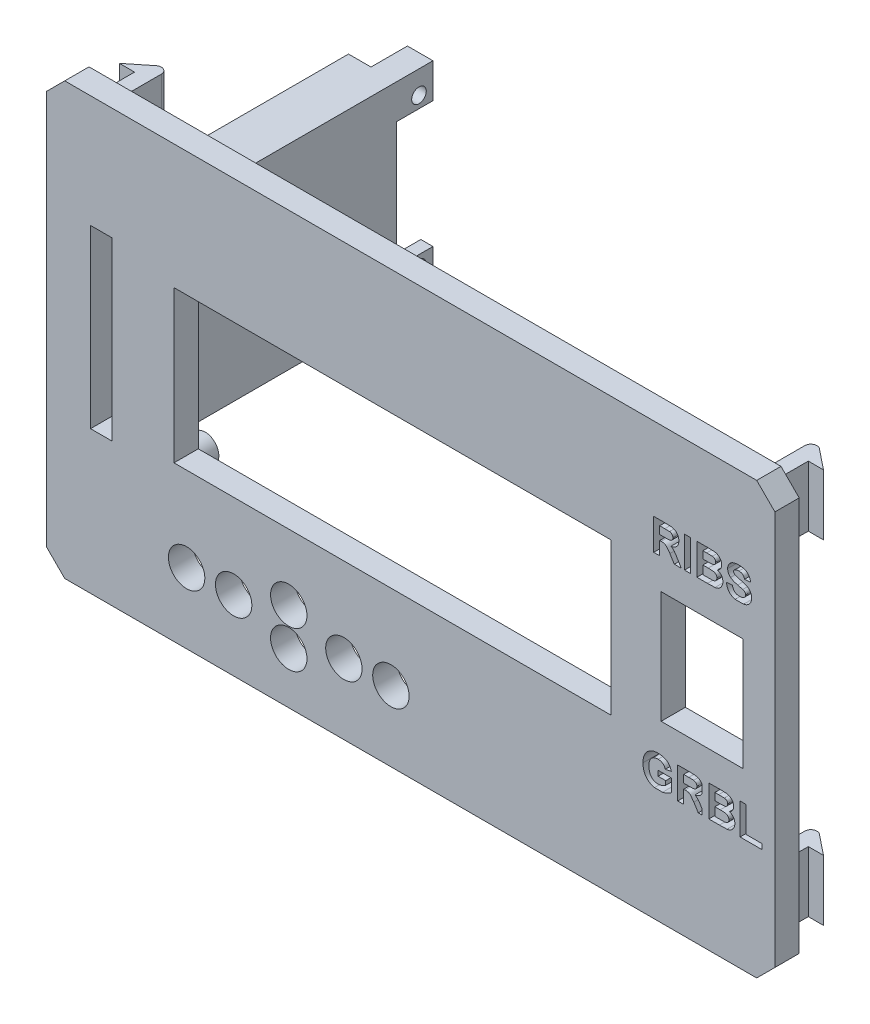
SolidWorks part; units mm, degrees
ref_plane "Спереди" through (0, 0, 0) normal (0, 0, 1) x (1, 0, 0)
ref_plane "Сверху" through (0, 0, 0) normal (0, 1, 0) x (1, 0, 0)
ref_plane "Справа" through (0, 0, 0) normal (1, 0, 0) x (0, 0, -1)
sketch "Эскиз1" plane through (0, 0, 0) normal (0, 0, 1) x (1, 0, 0)
  line L1 (-60, 30) -> (60, 30)
  line L2 (-60, 30) -> (-60, -30)
  line L3 (-60, -30) -> (60, -30)
  line L4 (60, 30) -> (60, -30)
  line L5 (-60, 30) -> (60, -30) construction
  line L6 (-60, -30) -> (60, 30) construction
  point P0 (0, 0)
  dimension "D1" = 120
  dimension "D2" = 60
extrude "Бобышка-Вытянуть1" add sketch "Эскиз1" along normal blind 4
sketch "Эскиз2" plane through (0, 0, 4) normal (0, 0, 1) x (1, 0, 0)
  line L0 (-60, 30) -> (-36, 30)
  line L1 (60, 30) -> (-60, 30) construction
  line L2 (-36, 30) -> (36, 30)
  line L3 (36, 30) -> (60, 30)
  line L4 (-36, 30) -> (-36, 12.5)
  line L5 (-36, 12.5) -> (-36, -12.5)
  line L6 (-36, -12.5) -> (-36, -30)
  line L7 (-60, -30) -> (60, -30) construction
  line L8 (-36, 12.5) -> (36, 12.5)
  line L9 (36, 12.5) -> (36, -12.5)
  line L10 (36, -12.5) -> (-36, -12.5)
  dimension "D1" = 72
  dimension "D2" = 25
extrude "Вырез-Вытянуть1" cut sketch "Эскиз2" against normal through all contours L10 L9 L8 L5
sketch "Эскиз3" plane through (0, 0, 4) normal (0, 0, 1) x (1, 0, 0)
  line L0 (51, 30) -> (51, -30)
  line L2 (51, 12.5) -> (51, 30)
  line L3 (60, 30) -> (-60, 30) construction
  line L4 (-60, -30) -> (60, -30) construction
  line L5 (51, 30) -> (60, 30)
  line L6 (44.25, 9.25) -> (57.75, 9.25)
  line L7 (44.25, 9.25) -> (44.25, -9.25)
  line L8 (44.25, -9.25) -> (57.75, -9.25)
  line L9 (57.75, 9.25) -> (57.75, -9.25)
  line L10 (44.25, 9.25) -> (57.75, -9.25) construction
  line L11 (44.25, -9.25) -> (57.75, 9.25) construction
  point P4 (51, 0)
  dimension "D1" = 13.5
  dimension "D2" = 18.5
  dimension "D3" = 9
extrude "Вырез-Вытянуть2" cut sketch "Эскиз3" against normal through all contours L9 L6 L0 L8 | L7 L8 L0 L6
sketch "Эскиз4" plane through (0, 0, 4) normal (0, 0, 1) x (1, 0, 0)
  line L0 (-60, 30) -> (-48, 30)
  line L1 (60, 30) -> (-60, 30) construction
  line L2 (-48, 30) -> (-48, -30)
  line L3 (-60, -30) -> (60, -30) construction
  line L5 (-49.75, 14.5) -> (-46.25, 14.5)
  line L6 (-49.75, 14.5) -> (-49.75, -14.5)
  line L7 (-49.75, -14.5) -> (-46.25, -14.5)
  line L8 (-46.25, 14.5) -> (-46.25, -14.5)
  line L9 (-49.75, 14.5) -> (-46.25, -14.5) construction
  line L10 (-49.75, -14.5) -> (-46.25, 14.5) construction
  point P8 (-48, 0)
  dimension "D1" = 12
  dimension "D2" = 3.5
  dimension "D3" = 29
extrude "Вырез-Вытянуть3" cut sketch "Эскиз4" against normal through all contours L8 L5 L2 L7 | L6 L7 L2 L5
sketch "Эскиз5" plane through (0, 30, 0) normal (0, 1, 0) x (1, 0, 0)
  line L1 (-60, 0) -> (60, 0)
  line L2 (-60, 0) -> (-60, -4)
  line L3 (-60, -4) -> (60, -4)
  line L4 (60, 0) -> (60, -4)
extrude "Бобышка-Вытянуть2" add sketch "Эскиз5" along normal blind 5
sketch "Эскиз6" plane through (0, -30, 0) normal (0, -1, 0) x (1, 0, 0)
  line L1 (-60, 0) -> (60, 0)
  line L2 (-60, 0) -> (-60, 4)
  line L3 (-60, 4) -> (60, 4)
  line L4 (60, 0) -> (60, 4)
extrude "Бобышка-Вытянуть3" add sketch "Эскиз6" along normal blind 10
sketch "Эскиз7" plane through (0, 0, 0) normal (0, 0, -1) x (-1, 0, 0)
  line L0 (60, -40) -> (33.92, -40)
  line L1 (60, -40) -> (-60, -40) construction
  line L2 (33.92, -40) -> (33.92, -26.42)
  circle A0 centre (33.92, -26.42) radius 2
  dimension "D3" = 4
  dimension "D1" = 26.08
  dimension "D2" = 13.58
extrude "Вырез-Вытянуть4" cut sketch "Эскиз7" against normal through all
sketch "Эскиз8" plane through (0, 0, 0) normal (0, 0, -1) x (-1, 0, 0)
  line L0 (33.92, -26.42) -> (26.173, -26.42)
  circle A0 centre (26.173, -26.42) radius 2
  dimension "D2" = 4
  dimension "D1" = 7.747
extrude "Вырез-Вытянуть5" cut sketch "Эскиз8" against normal through all
sketch "Эскиз10" plane through (0, 0, 0) normal (0, 0, -1) x (-1, 0, 0)
  line L0 (26.173, -26.42) -> (8.013, -26.42)
  line L1 (17.093, -26.42) -> (17.093, -29.4242)
  circle A0 centre (33.92, -26.42) radius 2
  circle A1 centre (26.173, -26.42) radius 2
  circle A2 centre (0.266, -26.42) radius 2
  circle A3 centre (8.013, -26.42) radius 2
  dimension "D1" = 18.16
extrude "Вырез-Вытянуть6" cut sketch "Эскиз10" against normal through all
sketch "Эскиз11" plane through (0, 0, 0) normal (0, 0, -1) x (-1, 0, 0)
  line L0 (26.173, -26.42) -> (8.013, -26.42)
  line L1 (17.093, -26.42) -> (17.093, -29.52)
  line L2 (17.093, -26.42) -> (17.093, -23.35)
  circle A0 centre (17.093, -29.52) radius 2
  circle A1 centre (17.093, -23.35) radius 2
  dimension "D3" = 4
  dimension "D4" = 4
  dimension "D1" = 3.07
  dimension "D2" = 3.1
extrude "Вырез-Вытянуть8" cut sketch "Эскиз11" against normal blind 10
sketch "Эскиз12" plane through (0, 0, 0) normal (0, 0, -1) x (-1, 0, 0)
  circle A0 centre (33.92, -26.42) radius 3
  circle A1 centre (26.173, -26.42) radius 3
  circle A2 centre (17.093, -29.52) radius 3
  circle A3 centre (17.093, -23.35) radius 3
  circle A4 centre (8.013, -26.42) radius 3
  circle A5 centre (0.266, -26.42) radius 3
  dimension "D1" = 6
extrude "Вырез-Вытянуть9" cut sketch "Эскиз12" against normal blind 10
sketch "Эскиз13" plane through (0, 0, 0) normal (0, 0, -1) x (-1, 0, 0)
  line L0 (46.25, -14.5) -> (37.86, -14.5)
  line L1 (37.86, -14.5) -> (37.86, -14.789)
  circle A0 centre (37.86, -14.789) radius 2.25
  circle A1 centre (-37.64, -14.789) radius 2.25
  circle A2 centre (-37.64, 16.711) radius 2.25
  circle A3 centre (37.86, 16.711) radius 2.25
  dimension "D2" = 4.5
  dimension "D1" = 8.39
  dimension "D3" = 2
  dimension "D4" = 2
extrude "Бобышка-Вытянуть4" add sketch "Эскиз13" along normal blind 3
sketch "Эскиз14" plane through (0, 0, 0) normal (0, 0, -1) x (-1, 0, 0)
  line L0 (37.86, 18.961) -> (-37.64, 18.961)
  line L1 (-37.64, 18.961) -> (-34.04, 18.961)
  line L2 (-34.04, 18.961) -> (-34.04, 15.961)
  line L3 (-34.04, 15.961) -> (34.26, 15.961)
  line L4 (34.26, 15.961) -> (34.26, 18.961)
  circle A0 centre (37.86, 16.711) radius 2.25 construction
  circle A1 centre (37.86, 16.711) radius 2.25 construction
  circle A2 centre (-37.64, 16.711) radius 2.25 construction
  circle A3 centre (-37.64, 16.711) radius 2.25 construction
  dimension "D1" = 3
  dimension "D2" = 3.6
  dimension "D3" = 3.6
extrude "Вырез-Вытянуть10" cut sketch "Эскиз14" against normal blind 2 contours L3 L4 L0 L2
sketch "Эскиз15" plane through (0, 0, -3) normal (0, 0, -1) x (-1, 0, 0)
  circle A0 centre (37.86, -14.789) radius 1.25
  circle A1 centre (37.86, 16.711) radius 1.25
  circle A2 centre (-37.64, 16.711) radius 1.25
  circle A3 centre (-37.64, -14.789) radius 1.25
  dimension "D1" = 2.5
extrude "Вырез-Вытянуть11" cut sketch "Эскиз15" against normal blind 6
sketch "Эскиз16" plane through (0, 0, 0) normal (0, 0, -1) x (-1, 0, 0)
  line L0 (49.75, -14.5) -> (49.75, 14.5)
  line L1 (51.25, 13.5693) -> (51.25, 16.2)
  line L2 (51.25, 13.5693) -> (51.25, -14.5)
  line L3 (49.75, 14.5) -> (45.3372, 14.5)
  line L4 (51.25, -14.5) -> (51.25, -16)
  line L5 (51.25, -16) -> (43.3372, -16)
  line L6 (43.3372, -16) -> (43.3372, 16.2)
  line L7 (51.25, 16.2) -> (43.3372, 16.2)
  line L8 (49.75, 14.5) -> (49.75, 14.7)
  line L9 (49.75, -14.5) -> (45.3372, -14.5)
  line L10 (45.3372, -14.5) -> (45.3372, 14.5)
  line L11 (49.75, 14.7) -> (45.3372, 14.7)
  line L12 (45.3372, 14.7) -> (45.3372, 14.5)
  line M40 (49.75, 14.5) -> (49.75, -14.5)
  line M41 (49.75, -14.5) -> (46.25, -14.5)
  dimension "D1" = 1.7
  dimension "D2" = 1.5
  dimension "D3" = 1.5
  dimension "D4" = 1.5
  dimension "D5" = 2
extrude "Бобышка-Вытянуть5" add sketch "Эскиз16" along normal blind 40 contours L1 L7 L6 L5 L4 L2 L12 L11 L8 L9 L10 M40 M41
sketch "Эскиз17" plane through (0, 0, -40) normal (0, 0, -1) x (-1, 0, 0)
  line L0 (47.5436, -14.5) -> (47.5436, -16)
  line L1 (49.75, -14.5) -> (45.3372, -14.5) construction
  line L2 (51.25, -16) -> (43.3372, -16) construction
  line L3 (47.5436, -16) -> (43.3372, -16)
  line L4 (43.3372, -16) -> (43.3372, -10.3)
  line L5 (43.3372, -16) -> (43.3372, 16.2) construction
  line L6 (43.3372, -10.3) -> (45.3372, -10.3)
  line L7 (45.3372, 14.7) -> (45.3372, -14.5) construction
  line L8 (45.3372, -10.3) -> (45.3372, -14.5)
  line L9 (45.3372, -14.5) -> (47.5436, -14.5)
  line L10 (45.3372, 0.1) -> (52.8332, 0.1)
  line L11 (45.3372, 14.7) -> (47.5436, 14.7)
  line L12 (45.3372, 10.5) -> (45.3372, 14.7)
  line L13 (43.3372, 10.5) -> (45.3372, 10.5)
  line L14 (43.3372, 16.2) -> (43.3372, 10.5)
  line L15 (47.5436, 16.2) -> (43.3372, 16.2)
  line L16 (47.5436, 14.7) -> (47.5436, 16.2)
  line M3 (45.3372, -14.5) -> (45.3372, 14.7)
  line M4 (45.3372, 14.7) -> (49.75, 14.7)
  line M6 (49.75, -14.5) -> (45.3372, -14.5)
  line M8 (51.25, 16.2) -> (43.3372, 16.2)
  line M9 (43.3372, 16.2) -> (43.3372, -16)
  line M10 (43.3372, -16) -> (51.25, -16)
  dimension "D1" = 5.7
extrude "Бобышка-Вытянуть6" add sketch "Эскиз17" along normal blind 6 contours L16 L13 M4 M8 M9 M3 | L6 L0 M9 M10 M6 M3
sketch "Эскиз18" plane through (-43.3372, 0, 0) normal (1, 0, 0) x (0, 0, -1)
  line L0 (46, -16) -> (43.7, -16)
  line L1 (46, -16) -> (0, -16) construction
  line L2 (43.7, -16) -> (43.7, 20.0976)
  line L3 (43.7, -16) -> (43.7, -12.216)
  line L4 (40, 0.1) -> (48.8407, 0.1)
  line L5 (40, -10.3) -> (40, 10.5) construction
  circle A0 centre (43.7, -12.216) radius 1.2
  circle A1 centre (43.7, 12.416) radius 1.2
  dimension "D3" = 2.4
  dimension "D1" = 2.3
  dimension "D2" = 3.784
extrude "Вырез-Вытянуть12" cut sketch "Эскиз18" against normal through all contours L2 A0 L3 | L3 A0 L2 | A1 L2 | A1 L2
sketch "Эскиз19" plane through (60, 0, 0) normal (1, 0, 0) x (0, 0, -1)
  line L1 (0, -40) -> (-4, -40)
  line L2 (0, -40) -> (0, 35)
  line L3 (0, 35) -> (-4, 35)
  line L4 (-4, -40) -> (-4, 35)
extrude "Бобышка-Вытянуть7" add sketch "Эскиз19" along normal blind 3
sketch "Эскиз20" plane through (-60, 0, 0) normal (-1, 0, 0) x (0, 0, 1)
  line L0 (0, 35) -> (4, 35) construction
  line L1 (4, -40) -> (0, -40)
  line L2 (4, -40) -> (4, 35)
  line L3 (4, 35) -> (0, 35)
  line L4 (0, -40) -> (0, 35)
extrude "Вырез-Вытянуть13" cut sketch "Эскиз20" against normal blind 3
sketch "Эскиз21" plane through (0, 0, 4) normal (0, 0, 1) x (1, 0, 0)
  line L0 (51, 9.25) -> (51, 14.25)
  line L1 (44.25, 9.25) -> (57.75, 9.25) construction
  line L2 (39.8485, 14.25) -> (62.1515, 14.25)
  line L3 (44.25, 0) -> (57.75, 0)
  line L4 (44.25, 9.25) -> (44.25, -9.25) construction
  line L5 (57.75, 9.25) -> (57.75, -9.25) construction
  line L6 (51, -9.25) -> (51, -19.25)
  line L7 (44.25, -9.25) -> (57.75, -9.25) construction
  line L8 (39.85, -19.25) -> (62.15, -19.25)
  line L9 (43.0316, 14.25) -> (43.0316, 19.3866)
  line L10 (43.0316, 19.3866) -> (45.1873, 19.3866)
  line L11 (46.953, 15.2666) -> (47.5756, 14.25)
  line L12 (47.5756, 14.25) -> (46.4211, 14.25)
  line L13 (46.4211, 14.25) -> (45.6905, 15.4158)
  line L14 (44.2407, 16.4232) -> (44.0194, 16.4232)
  line L15 (44.0194, 16.4232) -> (44.0194, 14.25)
  line L16 (44.0194, 14.25) -> (43.0316, 14.25)
  line L17 (44.0194, 17.2793) -> (44.8148, 17.2793)
  line L18 (44.8591, 18.5305) -> (44.0194, 18.5305)
  line L19 (44.0194, 18.5305) -> (44.0194, 17.2793)
  line L20 (48.1024, 14.25) -> (48.1024, 19.3866)
  line L21 (48.1024, 19.3866) -> (49.0902, 19.3866)
  line L22 (49.0902, 19.3866) -> (49.0902, 14.25)
  line L23 (49.0902, 14.25) -> (48.1024, 14.25)
  line L24 (50.1439, 19.3866) -> (52.2132, 19.3866)
  line L25 (51.8829, 14.25) -> (50.1439, 14.25)
  line L26 (50.1439, 14.25) -> (50.1439, 19.3866)
  line L27 (51.1317, 18.5305) -> (51.1317, 17.3452)
  line L28 (51.1317, 17.3452) -> (51.8468, 17.3452)
  line L29 (51.7584, 18.5305) -> (51.1317, 18.5305)
  line L30 (51.1317, 16.489) -> (51.1317, 15.1061)
  line L31 (51.1317, 15.1061) -> (52.1401, 15.1061)
  line L32 (52.0115, 16.489) -> (51.1317, 16.489)
  line L33 (55.0171, 15.9622) -> (56.0049, 16.0281)
  line L34 (58.9684, 17.9378) -> (57.9806, 17.872)
  line L35 (43.756, -17.3402) -> (43.756, -16.4841)
  line L36 (43.756, -16.4841) -> (45.9951, -16.4841)
  line L37 (45.9951, -16.4841) -> (45.9951, -18.5472)
  line L38 (45.9292, -15.5622) -> (44.9414, -15.7597)
  line L39 (45.0073, -18.0101) -> (45.0073, -17.3402)
  line L40 (45.0073, -17.3402) -> (43.756, -17.3402)
  line L41 (46.9829, -19.25) -> (46.9829, -14.1134)
  line L42 (46.9829, -14.1134) -> (49.1386, -14.1134)
  line L43 (50.9043, -18.2334) -> (51.5268, -19.25)
  line L44 (51.5268, -19.25) -> (50.3723, -19.25)
  line L45 (50.3723, -19.25) -> (49.6418, -18.0842)
  line L46 (48.1919, -17.0768) -> (47.9707, -17.0768)
  line L47 (47.9707, -17.0768) -> (47.9707, -19.25)
  line L48 (47.9707, -19.25) -> (46.9829, -19.25)
  line L49 (47.9707, -16.2207) -> (48.7661, -16.2207)
  line L50 (48.8103, -14.9695) -> (47.9707, -14.9695)
  line L51 (47.9707, -14.9695) -> (47.9707, -16.2207)
  line L52 (52.1195, -14.1134) -> (54.1888, -14.1134)
  line L53 (53.8585, -19.25) -> (52.1195, -19.25)
  line L54 (52.1195, -19.25) -> (52.1195, -14.1134)
  line L55 (53.1073, -14.9695) -> (53.1073, -16.1548)
  line L56 (53.1073, -16.1548) -> (53.8225, -16.1548)
  line L57 (53.734, -14.9695) -> (53.1073, -14.9695)
  line L58 (53.1073, -17.011) -> (53.1073, -18.3939)
  line L59 (53.1073, -18.3939) -> (54.1157, -18.3939)
  line L60 (53.9871, -17.011) -> (53.1073, -17.011)
  line L61 (57.2562, -19.25) -> (57.2562, -14.1134)
  line L62 (57.2562, -14.1134) -> (58.244, -14.1134)
  line L63 (58.244, -14.1134) -> (58.244, -18.3939)
  line L64 (58.244, -18.3939) -> (60.8781, -18.3939)
  line L65 (60.8781, -18.3939) -> (60.8781, -19.25)
  line L66 (60.8781, -19.25) -> (57.2562, -19.25)
  spline S0 degree 3 poles (45.1873, 19.3866) (45.3135, 19.386) (45.4963, 19.3844) (45.7301, 19.3679) (45.885, 19.3544) (46.0258, 19.3348) (46.1529, 19.3114) (46.2661, 19.2842) (46.3671, 19.2516) (46.4593, 19.2143) (46.5451, 19.17) (46.6255, 19.118) (46.7019, 19.0602) (46.7744, 18.9965) (46.8411, 18.9251) (46.9032, 18.8473) (46.9607, 18.7635) (47.0112, 18.6743) (47.0575, 18.5824) (47.0951, 18.4868) (47.1262, 18.3881) (47.151, 18.2864) (47.1744, 18.1449) (47.1809, 18.0365) (47.1804, 17.9636) knots 0 0 0 0 0.134568 0.194655 0.249727 0.300289 0.346032 0.387438 0.424316 0.459073 0.493245 0.527114 0.561039 0.595222 0.629875 0.664986 0.701286 0.737968 0.774262 0.810851 0.84727 0.884509 0.92231 1 1 1 1
  spline S1 degree 3 poles (47.1804, 17.9636) (47.1809, 17.8723) (47.1704, 17.7377) (47.1373, 17.5641) (47.1028, 17.4421) (47.0554, 17.3273) (47.0004, 17.2181) (46.9347, 17.1149) (46.8589, 17.0187) (46.773, 16.9294) (46.6766, 16.8489) (46.5705, 16.7768) (46.4539, 16.7136) (46.3278, 16.6596) (46.1414, 16.5973) (45.9938, 16.5667) (45.8922, 16.5508) knots 0 0 0 0 0.129362 0.190795 0.250525 0.308782 0.366645 0.423722 0.481911 0.540044 0.599083 0.659656 0.721689 0.786833 0.854049 1 1 1 1
  spline S2 degree 3 poles (45.8922, 16.5508) (45.9914, 16.4873) (46.1324, 16.3862) (46.2988, 16.2326) (46.3912, 16.1326) (46.4623, 16.0446) (46.5194, 15.9676) (46.5811, 15.879) (46.6467, 15.7788) (46.7181, 15.6678) (46.8218, 15.4963) (46.9001, 15.361) (46.953, 15.2666) knots 0 0 0 0 0.209649 0.307658 0.402219 0.451672 0.508779 0.572757 0.64366 0.721852 0.807549 1 1 1 1
  spline S3 degree 3 poles (45.6905, 15.4158) (45.6264, 15.505) (45.5349, 15.6323) (45.4158, 15.7911) (45.3413, 15.8916) (45.2732, 15.9769) (45.2135, 16.0487) (45.1634, 16.1083) (45.1067, 16.1674) (45.0408, 16.2281) (44.9592, 16.287) (44.8754, 16.334) (44.7856, 16.3698) (44.6818, 16.3948) (44.4991, 16.4182) (44.3489, 16.4245) (44.2407, 16.4232) knots 0 0 0 0 0.174865 0.249829 0.31616 0.3741 0.42377 0.464839 0.498075 0.554161 0.607388 0.658016 0.706819 0.760886 0.827647 1 1 1 1
  spline S4 degree 3 poles (44.8148, 17.2793) (44.9318, 17.2787) (45.0982, 17.282) (45.3081, 17.2864) (45.4381, 17.2941) (45.55, 17.3018) (45.6434, 17.3118) (45.7192, 17.3236) (45.7948, 17.3419) (45.8722, 17.3738) (45.9548, 17.4193) (46.0253, 17.4783) (46.0865, 17.5465) (46.1331, 17.6267) (46.1832, 17.7483) (46.1905, 17.8503) (46.1926, 17.9183) knots 0 0 0 0 0.20218 0.287584 0.36299 0.427194 0.481468 0.525327 0.559548 0.615694 0.669595 0.72182 0.77391 0.827085 0.881359 1 1 1 1
  spline S5 degree 3 poles (46.1926, 17.9183) (46.1917, 17.9941) (46.1784, 18.1071) (46.1144, 18.239) (46.0506, 18.3225) (45.9705, 18.3929) (45.8385, 18.4706) (45.7236, 18.5011) (45.6442, 18.5141) knots 0 0 0 0 0.256356 0.372788 0.488671 0.607002 0.72889 1 1 1 1
  spline S6 degree 3 poles (45.6442, 18.5141) (45.6118, 18.5183) (45.5544, 18.5209) (45.4672, 18.5249) (45.377, 18.5264) (45.2707, 18.5289) (45.0961, 18.5296) (44.9572, 18.5314) (44.8591, 18.5305) knots 0 0 0 0 0.124813 0.21921 0.333205 0.469464 0.625352 1 1 1 1
  spline S7 degree 3 poles (52.2132, 19.3866) (52.3092, 19.3858) (52.4485, 19.386) (52.6275, 19.3795) (52.747, 19.3755) (52.8563, 19.3661) (52.9562, 19.3587) (53.0465, 19.3486) (53.1529, 19.3321) (53.2766, 19.3066) (53.4163, 19.2593) (53.5487, 19.2003) (53.6719, 19.1252) (53.7862, 19.0374) (53.8925, 18.9375) (53.9859, 18.8216) (54.0701, 18.6951) (54.141, 18.5579) (54.2074, 18.3586) (54.227, 18.2007) (54.2269, 18.0942) knots 0 0 0 0 0.105884 0.153553 0.197457 0.237653 0.274456 0.307946 0.337788 0.393117 0.446926 0.500064 0.552657 0.605522 0.658748 0.713023 0.769236 0.826057 0.882736 1 1 1 1
  spline S8 degree 3 poles (54.2269, 18.0942) (54.2277, 17.9776) (54.2045, 17.8031) (54.1255, 17.5835) (54.043, 17.4299) (53.9417, 17.2889) (53.7817, 17.1228) (53.6357, 17.0282) (53.5313, 16.9799) knots 0 0 0 0 0.252157 0.376787 0.502926 0.628342 0.751132 1 1 1 1
  spline S9 degree 3 poles (53.5313, 16.9799) (53.6004, 16.9575) (53.7011, 16.9191) (53.8258, 16.8515) (53.9119, 16.7963) (53.9924, 16.7353) (54.0649, 16.6667) (54.1336, 16.5942) (54.194, 16.5142) (54.2486, 16.4306) (54.2949, 16.3421) (54.3351, 16.2507) (54.3686, 16.1556) (54.3925, 16.0562) (54.4185, 15.9178) (54.423, 15.8107) (54.4244, 15.7389) knots 0 0 0 0 0.132557 0.19578 0.258217 0.318868 0.379478 0.440087 0.500739 0.561785 0.621919 0.682673 0.743576 0.805446 0.868975 1 1 1 1
  spline S10 degree 3 poles (54.4244, 15.7389) (54.4237, 15.6231) (54.4048, 15.4477) (54.3353, 15.2222) (54.2649, 15.0565) (54.1773, 14.9002) (54.0744, 14.7576) (53.9543, 14.6334) (53.8213, 14.5241) (53.6714, 14.4336) (53.4431, 14.3379) (53.2567, 14.2984) (53.1279, 14.285) knots 0 0 0 0 0.162135 0.244884 0.329397 0.413636 0.495044 0.574817 0.654649 0.735398 0.818839 1 1 1 1
  spline S11 degree 3 poles (53.1279, 14.285) (53.0697, 14.2798) (52.971, 14.2728) (52.824, 14.2672) (52.68, 14.2617) (52.5129, 14.2578) (52.2447, 14.2539) (52.0321, 14.2505) (51.8829, 14.25) knots 0 0 0 0 0.140766 0.238316 0.354022 0.487867 0.640687 1 1 1 1
  spline S12 degree 3 poles (51.8468, 17.3452) (51.9429, 17.3444) (52.0794, 17.3459) (52.2516, 17.3469) (52.3583, 17.3488) (52.4498, 17.3521) (52.5415, 17.3558) (52.6026, 17.3585) (52.6381, 17.3626) knots 0 0 0 0 0.363929 0.517302 0.652498 0.76824 0.864499 1 1 1 1
  spline S13 degree 3 poles (52.6381, 17.3626) (52.7233, 17.3736) (52.8478, 17.3988) (52.9915, 17.4745) (53.0806, 17.5423) (53.1512, 17.6256) (53.2224, 17.7565) (53.2385, 17.8703) (53.239, 17.9461) knots 0 0 0 0 0.279181 0.403147 0.522445 0.638838 0.753413 1 1 1 1
  spline S14 degree 3 poles (53.239, 17.9461) (53.2409, 18.0195) (53.2235, 18.1269) (53.1644, 18.2553) (53.102, 18.3358) (53.0236, 18.4038) (52.8896, 18.4782) (52.7716, 18.5018) (52.6906, 18.513) knots 0 0 0 0 0.250586 0.366014 0.479792 0.596199 0.718553 1 1 1 1
  spline S15 degree 3 poles (52.6906, 18.513) (52.6509, 18.5173) (52.5819, 18.5199) (52.4773, 18.5236) (52.3703, 18.5269) (52.244, 18.5288) (52.0379, 18.5298) (51.8739, 18.5313) (51.7584, 18.5305) knots 0 0 0 0 0.12824 0.222081 0.336875 0.472602 0.628175 1 1 1 1
  spline S16 degree 3 poles (52.1401, 15.1061) (52.2293, 15.1044) (52.3565, 15.1079) (52.5171, 15.1094) (52.6176, 15.1142) (52.7044, 15.1179) (52.7935, 15.1235) (52.853, 15.1321) (52.8882, 15.138) knots 0 0 0 0 0.356994 0.509418 0.64271 0.759541 0.857263 1 1 1 1
  spline S17 degree 3 poles (52.8882, 15.138) (52.9649, 15.1503) (53.0748, 15.1871) (53.2039, 15.2669) (53.2863, 15.3419) (53.3539, 15.4318) (53.4216, 15.5767) (53.4371, 15.6999) (53.4366, 15.7832) knots 0 0 0 0 0.250408 0.369283 0.487615 0.607843 0.730168 1 1 1 1
  spline S18 degree 3 poles (53.4366, 15.7832) (53.437, 15.856) (53.4238, 15.9632) (53.3724, 16.0939) (53.3203, 16.1799) (53.2552, 16.2573) (53.1747, 16.3222) (53.0817, 16.3762) (52.9931, 16.4118) (52.9091, 16.4346) (52.8289, 16.4496) (52.7323, 16.4614) (52.6197, 16.4714) (52.4907, 16.4795) (52.2863, 16.4884) (52.1247, 16.4885) (52.0115, 16.489) knots 0 0 0 0 0.120696 0.176255 0.231267 0.286442 0.342925 0.401446 0.463858 0.500356 0.545451 0.598688 0.661396 0.732508 0.81263 1 1 1 1
  spline S19 degree 3 poles (56.0049, 16.0281) (56.018, 15.9473) (56.048, 15.8317) (56.0995, 15.6854) (56.1441, 15.5876) (56.193, 15.497) (56.2502, 15.4159) (56.3116, 15.342) (56.3803, 15.2778) (56.4552, 15.2216) (56.5366, 15.1736) (56.6236, 15.1321) (56.7165, 15.098) (56.8162, 15.0725) (56.9605, 15.0476) (57.0728, 15.0405) (57.1491, 15.0403) knots 0 0 0 0 0.146236 0.213456 0.277502 0.33853 0.397652 0.454745 0.510362 0.565639 0.622097 0.67924 0.738115 0.799044 0.863264 1 1 1 1
  spline S20 degree 3 poles (57.1491, 15.0403) (57.2293, 15.0395) (57.3457, 15.0464) (57.4951, 15.068) (57.5951, 15.0925) (57.6886, 15.12) (57.773, 15.1577) (57.8499, 15.2011) (57.919, 15.2503) (57.9793, 15.3049) (58.0321, 15.3619) (58.078, 15.4201) (58.1142, 15.482) (58.1434, 15.5452) (58.1695, 15.634) (58.1785, 15.7027) (58.1781, 15.7492) knots 0 0 0 0 0.172353 0.250759 0.324349 0.393928 0.460037 0.522848 0.58369 0.642236 0.697606 0.750761 0.801402 0.851621 0.900196 1 1 1 1
  spline S21 degree 3 poles (58.1781, 15.7492) (58.1795, 15.8066) (58.1655, 15.8908) (58.1208, 15.9937) (58.0716, 16.0625) (58.0054, 16.1253) (57.8845, 16.2096) (57.7744, 16.2534) (57.6966, 16.2822) knots 0 0 0 0 0.2213 0.325895 0.431605 0.54614 0.677623 1 1 1 1
  spline S22 degree 3 poles (57.6966, 16.2822) (57.657, 16.2962) (57.5891, 16.3154) (57.4892, 16.3444) (57.3923, 16.3715) (57.2803, 16.3992) (57.103, 16.4473) (56.9615, 16.4794) (56.8631, 16.5055) knots 0 0 0 0 0.145969 0.245215 0.361498 0.495676 0.646055 1 1 1 1
  spline S23 degree 3 poles (56.8631, 16.5055) (56.7325, 16.5358) (56.546, 16.5903) (56.3093, 16.67) (56.1547, 16.7322) (56.0148, 16.7952) (55.8571, 16.882) (55.7509, 16.9557) (55.689, 17.0097) knots 0 0 0 0 0.312041 0.452204 0.58122 0.699855 0.809224 1 1 1 1
  spline S24 degree 3 poles (55.689, 17.0097) (55.6139, 17.0774) (55.509, 17.1852) (55.3981, 17.3484) (55.3307, 17.4741) (55.2789, 17.6061) (55.2291, 17.7913) (55.2139, 17.9361) (55.2147, 18.0335) knots 0 0 0 0 0.260864 0.384835 0.506941 0.627504 0.749214 1 1 1 1
  spline S25 degree 3 poles (55.2147, 18.0335) (55.2135, 18.1606) (55.2423, 18.3513) (55.3337, 18.5915) (55.4124, 18.7345) (55.4883, 18.8427) (55.5512, 18.9204) (55.6204, 18.9931) (55.6967, 19.059) (55.7774, 19.1221) (55.8654, 19.178) (55.9585, 19.2308) (56.0931, 19.2933) (56.2759, 19.3584) (56.6045, 19.4346) (56.8659, 19.4517) (57.0452, 19.4525) knots 0 0 0 0 0.146314 0.219931 0.295355 0.333985 0.372228 0.410559 0.449522 0.48845 0.5285 0.569766 0.611707 0.699547 0.793005 1 1 1 1
  spline S26 degree 3 poles (57.0452, 19.4525) (57.1934, 19.453) (57.4091, 19.4414) (57.6851, 19.3982) (57.8709, 19.3535) (58.0419, 19.2943) (58.1987, 19.2239) (58.3413, 19.1402) (58.468, 19.0429) (58.5808, 18.9356) (58.6792, 18.8184) (58.7636, 18.6928) (58.8345, 18.5588) (58.8902, 18.4158) (58.9459, 18.2098) (58.9638, 18.0477) (58.9684, 17.9378) knots 0 0 0 0 0.161084 0.23435 0.303453 0.368554 0.430806 0.490159 0.547891 0.604075 0.659129 0.713948 0.768331 0.823595 0.880408 1 1 1 1
  spline S27 degree 3 poles (57.9806, 17.872) (57.9708, 17.9326) (57.9499, 18.02) (57.9124, 18.1298) (57.8805, 18.2032) (57.842, 18.2689) (57.8001, 18.3288) (57.7536, 18.3822) (57.7011, 18.4275) (57.6442, 18.4688) (57.5794, 18.5019) (57.5094, 18.5326) (57.4315, 18.5557) (57.3473, 18.574) (57.2222, 18.5927) (57.1245, 18.595) (57.0576, 18.5964) knots 0 0 0 0 0.140207 0.204905 0.264912 0.322857 0.378531 0.431843 0.484049 0.536898 0.59195 0.649895 0.711385 0.777189 0.846914 1 1 1 1
  spline S28 degree 3 poles (57.0576, 18.5964) (56.9875, 18.5956) (56.885, 18.592) (56.7535, 18.5718) (56.6635, 18.5528) (56.5796, 18.5268) (56.4775, 18.4855) (56.4072, 18.4446) (56.364, 18.4143) knots 0 0 0 0 0.288592 0.421401 0.547152 0.666859 0.782766 1 1 1 1
  spline S29 degree 3 poles (56.364, 18.4143) (56.3141, 18.3795) (56.2274, 18.2869) (56.2027, 18.1627) (56.2025, 18.1025) knots 0 0 0 0 0.502502 1 1 1 1
  spline S30 degree 3 poles (56.2025, 18.1025) (56.2012, 18.0451) (56.2297, 17.9273) (56.308, 17.8351) (56.3548, 17.7969) knots 0 0 0 0 0.485261 1 1 1 1
  spline S31 degree 3 poles (56.3548, 17.7969) (56.3949, 17.7639) (56.4697, 17.7222) (56.5825, 17.6702) (56.692, 17.6284) (56.8186, 17.5869) (56.9623, 17.5435) (57.1232, 17.4995) (57.2972, 17.4569) (57.4738, 17.415) (57.6424, 17.3692) (57.7992, 17.3245) (57.9433, 17.2778) (58.0757, 17.2322) (58.1957, 17.1854) (58.304, 17.1399) (58.4303, 17.0772) (58.5734, 16.9923) (58.7234, 16.869) (58.8561, 16.7303) (58.9486, 16.5996) (59.0121, 16.4871) (59.053, 16.3975) (59.0883, 16.303) (59.1171, 16.2036) (59.138, 16.0992) (59.1615, 15.9515) (59.1653, 15.8371) (59.1659, 15.7595) knots 0 0 0 0 0.040851 0.06742 0.098236 0.13339 0.172761 0.216898 0.265232 0.314356 0.360395 0.4033 0.443173 0.480216 0.513952 0.544926 0.573058 0.625371 0.67606 0.726118 0.776675 0.802168 0.82813 0.85447 0.881844 0.909815 0.938613 1 1 1 1
  spline S32 degree 3 poles (59.1659, 15.7595) (59.1657, 15.6872) (59.158, 15.5795) (59.1334, 15.4382) (59.1065, 15.3347) (59.0708, 15.2331) (59.0306, 15.132) (58.9803, 15.0336) (58.923, 14.9379) (58.8599, 14.8448) (58.7883, 14.759) (58.7125, 14.6775) (58.6277, 14.6049) (58.5391, 14.5354) (58.4426, 14.4738) (58.3405, 14.4181) (58.2322, 14.3687) (58.1172, 14.3256) (57.9957, 14.2872) (57.8667, 14.2558) (57.7311, 14.2289) (57.5886, 14.2085) (57.3852, 14.189) (57.2288, 14.1848) (57.1224, 14.1841) knots 0 0 0 0 0.074519 0.111158 0.147709 0.184737 0.222181 0.259833 0.298539 0.337199 0.375653 0.413687 0.45179 0.490635 0.529785 0.569677 0.610518 0.6525 0.696246 0.741804 0.789396 0.838723 0.890254 1 1 1 1
  spline S33 degree 3 poles (57.1224, 14.1841) (56.97, 14.1838) (56.7477, 14.1973) (56.4628, 14.2443) (56.2692, 14.2937) (56.0895, 14.3572) (55.9237, 14.4354) (55.7727, 14.5288) (55.6344, 14.6352) (55.5109, 14.7563) (55.3999, 14.8899) (55.3028, 15.037) (55.2196, 15.1974) (55.1485, 15.3702) (55.0681, 15.6234) (55.034, 15.8248) (55.0171, 15.9622) knots 0 0 0 0 0.148212 0.216241 0.280668 0.34231 0.401421 0.458656 0.514793 0.570722 0.626653 0.683482 0.741844 0.802144 0.865151 1 1 1 1
  spline S34 degree 3 poles (45.9951, -18.5472) (45.9382, -18.5999) (45.8468, -18.6764) (45.7118, -18.7675) (45.5992, -18.8352) (45.4783, -18.902) (45.3483, -18.9661) (45.2087, -19.0262) (45.0132, -19.1059) (44.7599, -19.1889) (44.3497, -19.2873) (44.0353, -19.3156) (43.827, -19.3159) knots 0 0 0 0 0.09909 0.152123 0.208003 0.267082 0.328665 0.393275 0.461354 0.598507 0.733703 1 1 1 1
  spline S35 degree 3 poles (43.827, -19.3159) (43.6986, -19.3155) (43.5081, -19.3069) (43.2604, -19.2708) (43.0837, -19.2331) (42.9127, -19.1877) (42.7483, -19.1298) (42.591, -19.0603) (42.4394, -18.9828) (42.2963, -18.8938) (42.1616, -18.7965) (42.0362, -18.6899) (41.9207, -18.574) (41.8134, -18.4494) (41.7155, -18.3156) (41.6278, -18.1725) (41.5491, -18.0217) (41.4791, -17.8647) (41.42, -17.7027) (41.3682, -17.5381) (41.3257, -17.3702) (41.2944, -17.1985) (41.2616, -16.9637) (41.255, -16.7843) (41.2536, -16.6642) knots 0 0 0 0 0.092398 0.13676 0.179854 0.222268 0.26384 0.30503 0.345839 0.386148 0.426054 0.465241 0.504301 0.543648 0.583355 0.623324 0.664248 0.705537 0.746812 0.788151 0.8296 0.871245 0.91355 1 1 1 1
  spline S36 degree 3 poles (41.2536, -16.6642) (41.2534, -16.535) (41.2635, -16.3434) (41.2974, -16.0931) (41.3352, -15.9136) (41.3812, -15.7393) (41.4374, -15.5701) (41.5062, -15.4074) (41.5828, -15.2498) (41.6699, -15.0995) (41.7684, -14.9583) (41.8753, -14.8249) (41.9927, -14.7014) (42.1202, -14.5878) (42.3034, -14.4465) (42.4521, -14.3542) (42.5573, -14.3017) knots 0 0 0 0 0.136153 0.201841 0.266068 0.329284 0.391808 0.453702 0.515293 0.576359 0.636621 0.696516 0.756344 0.81599 0.876288 1 1 1 1
  spline S37 degree 3 poles (42.5573, -14.3017) (42.6404, -14.2573) (42.7731, -14.2032) (42.9577, -14.1437) (43.1063, -14.1097) (43.2622, -14.0818) (43.4842, -14.0534) (43.6555, -14.0485) (43.7715, -14.0475) knots 0 0 0 0 0.225442 0.342643 0.464218 0.590259 0.721935 1 1 1 1
  spline S38 degree 3 poles (43.7715, -14.0475) (43.9202, -14.0479) (44.1381, -14.0574) (44.418, -14.1012) (44.6097, -14.145) (44.7885, -14.2014) (44.9541, -14.2707) (45.1075, -14.3515) (45.2465, -14.4471) (45.3739, -14.5526) (45.4894, -14.6679) (45.593, -14.7934) (45.6848, -14.9284) (45.764, -15.0734) (45.8565, -15.2815) (45.9043, -15.4482) (45.9292, -15.5622) knots 0 0 0 0 0.154508 0.225881 0.293868 0.358517 0.420293 0.480039 0.538219 0.595126 0.651534 0.707437 0.763839 0.820741 0.878777 1 1 1 1
  spline S39 degree 3 poles (44.9414, -15.7597) (44.9234, -15.6954) (44.8902, -15.6018) (44.8318, -15.4853) (44.783, -15.4038) (44.7278, -15.3278) (44.6651, -15.2579) (44.5986, -15.1911) (44.5242, -15.1319) (44.4449, -15.0786) (44.3616, -15.0305) (44.2724, -14.9915) (44.1785, -14.9601) (44.0805, -14.9335) (43.94, -14.911) (43.8318, -14.9021) (43.7581, -14.9036) knots 0 0 0 0 0.126732 0.187869 0.247151 0.306787 0.365822 0.425205 0.485392 0.545878 0.606517 0.667724 0.730306 0.794256 0.860288 1 1 1 1
  spline S40 degree 3 poles (43.7581, -14.9036) (43.6477, -14.905) (43.4849, -14.9147) (43.2773, -14.9616) (43.1338, -15.0088) (42.9987, -15.0694) (42.874, -15.1457) (42.7564, -15.2331) (42.6494, -15.3357) (42.5523, -15.4507) (42.4683, -15.5796) (42.3984, -15.7218) (42.3411, -15.8767) (42.2955, -16.0444) (42.2527, -16.2933) (42.2407, -16.4882) (42.2414, -16.622) knots 0 0 0 0 0.127318 0.186832 0.24467 0.301065 0.356888 0.412745 0.469466 0.527226 0.585734 0.646153 0.709402 0.775714 0.845921 1 1 1 1
  spline S41 degree 3 poles (42.2414, -16.622) (42.2412, -16.766) (42.2518, -16.9758) (42.2965, -17.2435) (42.343, -17.4235) (42.4014, -17.5896) (42.4717, -17.7424) (42.5584, -17.879) (42.6561, -18.0021) (42.7652, -18.1098) (42.8829, -18.2036) (43.0082, -18.2831) (43.1426, -18.3471) (43.2841, -18.398) (43.4881, -18.4467) (43.6478, -18.4598) (43.756, -18.4597) knots 0 0 0 0 0.160106 0.232808 0.301325 0.366436 0.428344 0.487788 0.545837 0.602718 0.657791 0.71279 0.767354 0.822823 0.879689 1 1 1 1
  spline S42 degree 3 poles (43.756, -18.4597) (43.8687, -18.4604) (44.0386, -18.4415) (44.2624, -18.3895) (44.4283, -18.3307) (44.5894, -18.2631) (44.7862, -18.1618) (44.9245, -18.0762) (45.0073, -18.0101) knots 0 0 0 0 0.249644 0.377965 0.509161 0.639801 0.765422 1 1 1 1
  spline S43 degree 3 poles (49.1386, -14.1134) (49.2648, -14.114) (49.4476, -14.1156) (49.6813, -14.1321) (49.8363, -14.1456) (49.977, -14.1652) (50.1041, -14.1886) (50.2174, -14.2158) (50.3184, -14.2484) (50.4105, -14.2857) (50.4963, -14.33) (50.5768, -14.382) (50.6531, -14.4398) (50.7256, -14.5035) (50.7924, -14.5749) (50.8545, -14.6527) (50.9119, -14.7365) (50.9625, -14.8257) (51.0087, -14.9176) (51.0464, -15.0132) (51.0774, -15.1119) (51.1022, -15.2136) (51.1256, -15.3551) (51.1322, -15.4635) (51.1317, -15.5364) knots 0 0 0 0 0.134568 0.194655 0.249727 0.300289 0.346032 0.387438 0.424316 0.459073 0.493245 0.527114 0.561039 0.595222 0.629875 0.664986 0.701286 0.737968 0.774262 0.810851 0.84727 0.884509 0.92231 1 1 1 1
  spline S44 degree 3 poles (51.1317, -15.5364) (51.1322, -15.6277) (51.1216, -15.7623) (51.0885, -15.9359) (51.0541, -16.0579) (51.0067, -16.1727) (50.9516, -16.2819) (50.886, -16.3851) (50.8102, -16.4813) (50.7243, -16.5706) (50.6279, -16.6511) (50.5218, -16.7232) (50.4052, -16.7864) (50.279, -16.8404) (50.0927, -16.9027) (49.9451, -16.9333) (49.8434, -16.9492) knots 0 0 0 0 0.129362 0.190795 0.250525 0.308782 0.366645 0.423722 0.481911 0.540044 0.599083 0.659656 0.721689 0.786833 0.854049 1 1 1 1
  spline S45 degree 3 poles (49.8434, -16.9492) (49.9426, -17.0127) (50.0837, -17.1138) (50.25, -17.2674) (50.3425, -17.3674) (50.4135, -17.4554) (50.4707, -17.5324) (50.5324, -17.621) (50.598, -17.7212) (50.6694, -17.8322) (50.773, -18.0037) (50.8513, -18.139) (50.9043, -18.2334) knots 0 0 0 0 0.209649 0.307658 0.402219 0.451672 0.508779 0.572757 0.64366 0.721852 0.807549 1 1 1 1
  spline S46 degree 3 poles (49.6418, -18.0842) (49.5777, -17.995) (49.4862, -17.8677) (49.3671, -17.7089) (49.2926, -17.6084) (49.2245, -17.5231) (49.1647, -17.4513) (49.1147, -17.3917) (49.058, -17.3326) (48.9921, -17.2719) (48.9105, -17.213) (48.8267, -17.166) (48.7369, -17.1302) (48.6331, -17.1052) (48.4503, -17.0818) (48.3002, -17.0755) (48.1919, -17.0768) knots 0 0 0 0 0.174865 0.249829 0.31616 0.3741 0.42377 0.464839 0.498075 0.554161 0.607388 0.658016 0.706819 0.760886 0.827647 1 1 1 1
  spline S47 degree 3 poles (48.7661, -16.2207) (48.8831, -16.2213) (49.0494, -16.218) (49.2594, -16.2136) (49.3894, -16.2059) (49.5013, -16.1982) (49.5947, -16.1882) (49.6704, -16.1764) (49.746, -16.1581) (49.8235, -16.1262) (49.906, -16.0807) (49.9766, -16.0217) (50.0377, -15.9535) (50.0843, -15.8733) (50.1345, -15.7517) (50.1418, -15.6497) (50.1439, -15.5817) knots 0 0 0 0 0.20218 0.287584 0.36299 0.427194 0.481468 0.525327 0.559548 0.615694 0.669595 0.72182 0.77391 0.827085 0.881359 1 1 1 1
  spline S48 degree 3 poles (50.1439, -15.5817) (50.1429, -15.5059) (50.1297, -15.3929) (50.0656, -15.261) (50.0019, -15.1775) (49.9217, -15.1071) (49.7897, -15.0294) (49.6749, -14.9989) (49.5955, -14.9859) knots 0 0 0 0 0.256356 0.372788 0.488671 0.607002 0.72889 1 1 1 1
  spline S49 degree 3 poles (49.5955, -14.9859) (49.563, -14.9817) (49.5056, -14.9791) (49.4185, -14.9751) (49.3283, -14.9736) (49.2219, -14.9711) (49.0473, -14.9704) (48.9084, -14.9686) (48.8103, -14.9695) knots 0 0 0 0 0.124813 0.21921 0.333205 0.469464 0.625352 1 1 1 1
  spline S50 degree 3 poles (54.1888, -14.1134) (54.2848, -14.1142) (54.4241, -14.114) (54.6031, -14.1205) (54.7226, -14.1245) (54.8319, -14.1339) (54.9319, -14.1413) (55.0221, -14.1514) (55.1285, -14.1679) (55.2522, -14.1934) (55.3919, -14.2407) (55.5243, -14.2997) (55.6475, -14.3748) (55.7618, -14.4626) (55.8681, -14.5625) (55.9615, -14.6784) (56.0457, -14.8049) (56.1166, -14.9421) (56.183, -15.1414) (56.2026, -15.2993) (56.2025, -15.4058) knots 0 0 0 0 0.105884 0.153553 0.197457 0.237653 0.274456 0.307946 0.337788 0.393117 0.446926 0.500064 0.552657 0.605522 0.658748 0.713023 0.769236 0.826057 0.882736 1 1 1 1
  spline S51 degree 3 poles (56.2025, -15.4058) (56.2033, -15.5224) (56.1802, -15.6969) (56.1012, -15.9165) (56.0186, -16.0701) (55.9173, -16.2111) (55.7573, -16.3772) (55.6113, -16.4718) (55.5069, -16.5201) knots 0 0 0 0 0.252157 0.376787 0.502926 0.628342 0.751132 1 1 1 1
  spline S52 degree 3 poles (55.5069, -16.5201) (55.576, -16.5425) (55.6768, -16.5809) (55.8015, -16.6485) (55.8876, -16.7037) (55.968, -16.7647) (56.0405, -16.8333) (56.1093, -16.9058) (56.1696, -16.9858) (56.2242, -17.0694) (56.2705, -17.1579) (56.3107, -17.2493) (56.3443, -17.3444) (56.3682, -17.4438) (56.3941, -17.5822) (56.3986, -17.6893) (56.4001, -17.7611) knots 0 0 0 0 0.132557 0.19578 0.258217 0.318868 0.379478 0.440087 0.500739 0.561785 0.621919 0.682673 0.743576 0.805446 0.868975 1 1 1 1
  spline S53 degree 3 poles (56.4001, -17.7611) (56.3994, -17.8769) (56.3804, -18.0523) (56.3109, -18.2778) (56.2405, -18.4435) (56.1529, -18.5998) (56.05, -18.7424) (55.9299, -18.8666) (55.7969, -18.9759) (55.6471, -19.0664) (55.4188, -19.1621) (55.2323, -19.2016) (55.1035, -19.215) knots 0 0 0 0 0.162135 0.244884 0.329397 0.413636 0.495044 0.574817 0.654649 0.735398 0.818839 1 1 1 1
  spline S54 degree 3 poles (55.1035, -19.215) (55.0453, -19.2202) (54.9466, -19.2272) (54.7997, -19.2328) (54.6556, -19.2383) (54.4886, -19.2422) (54.2204, -19.2461) (54.0077, -19.2495) (53.8585, -19.25) knots 0 0 0 0 0.140766 0.238316 0.354022 0.487867 0.640687 1 1 1 1
  spline S55 degree 3 poles (53.8225, -16.1548) (53.9185, -16.1556) (54.055, -16.1541) (54.2272, -16.1531) (54.3339, -16.1512) (54.4255, -16.1479) (54.5171, -16.1442) (54.5782, -16.1415) (54.6138, -16.1374) knots 0 0 0 0 0.363929 0.517302 0.652498 0.76824 0.864499 1 1 1 1
  spline S56 degree 3 poles (54.6138, -16.1374) (54.699, -16.1264) (54.8234, -16.1012) (54.9671, -16.0255) (55.0562, -15.9577) (55.1268, -15.8744) (55.198, -15.7435) (55.2141, -15.6297) (55.2147, -15.5539) knots 0 0 0 0 0.279181 0.403147 0.522445 0.638838 0.753413 1 1 1 1
  spline S57 degree 3 poles (55.2147, -15.5539) (55.2165, -15.4805) (55.1991, -15.3731) (55.14, -15.2447) (55.0776, -15.1642) (54.9993, -15.0962) (54.8652, -15.0218) (54.7472, -14.9982) (54.6662, -14.987) knots 0 0 0 0 0.250586 0.366014 0.479792 0.596199 0.718553 1 1 1 1
  spline S58 degree 3 poles (54.6662, -14.987) (54.6266, -14.9827) (54.5576, -14.9801) (54.4529, -14.9764) (54.3459, -14.9731) (54.2197, -14.9712) (54.0135, -14.9702) (53.8496, -14.9687) (53.734, -14.9695) knots 0 0 0 0 0.12824 0.222081 0.336875 0.472602 0.628175 1 1 1 1
  spline S59 degree 3 poles (54.1157, -18.3939) (54.2049, -18.3956) (54.3322, -18.3921) (54.4927, -18.3906) (54.5932, -18.3858) (54.68, -18.3821) (54.7691, -18.3765) (54.8286, -18.3679) (54.8638, -18.362) knots 0 0 0 0 0.356994 0.509418 0.64271 0.759541 0.857263 1 1 1 1
  spline S60 degree 3 poles (54.8638, -18.362) (54.9406, -18.3497) (55.0504, -18.3129) (55.1795, -18.2331) (55.2619, -18.1581) (55.3295, -18.0682) (55.3972, -17.9233) (55.4127, -17.8001) (55.4122, -17.7168) knots 0 0 0 0 0.250408 0.369283 0.487615 0.607843 0.730168 1 1 1 1
  spline S61 degree 3 poles (55.4122, -17.7168) (55.4127, -17.644) (55.3995, -17.5368) (55.348, -17.4061) (55.296, -17.3201) (55.2308, -17.2427) (55.1503, -17.1778) (55.0573, -17.1238) (54.9687, -17.0882) (54.8847, -17.0654) (54.8045, -17.0504) (54.7079, -17.0386) (54.5954, -17.0286) (54.4663, -17.0205) (54.262, -17.0116) (54.1003, -17.0115) (53.9871, -17.011) knots 0 0 0 0 0.120696 0.176255 0.231267 0.286442 0.342925 0.401446 0.463858 0.500356 0.545451 0.598688 0.661396 0.732508 0.81263 1 1 1 1
  point P6 (51, 14.25)
  point P20 (51, -19.25)
  dimension "D1" = 5
  dimension "D2" = 22.3
  dimension "D3" = 10
extrude "Вырез-Вытянуть15" cut sketch "Эскиз21" against normal blind 3 contours L65 L64 L63 L62 L61 L8 | S54 S53 S52 S51 S50 L52 L54 L8 S61 S60 S59 L59 L58 L60 S58 S57 S56 S55 L56 L55 L57 | S46 L45 L8 L6 L43 S45 S44 S43 L42 L41 L47 L46 S49 S48 S47 L49 L51 L50 | S42 S41 S40 S39 L38 S38 S37 S36 S35 L8 S34 L37 L36 L35 L40 L39 | S33 L2 S32 S31 S30 S29 S28 S27 L34 S26 S25 S24 S23 S22 S21 S20 S19 L33 | S11 S10 S9 S8 S7 L24 L26 L2 S18 S17 S16 L31 L30 L32 S15 S14 S13 S12 L28 L27 L29 | L22 L21 L20 L2 | S3 L13 L2 L11 S2 S1 S0 L10 L9 L15 L14 S6 S5 S4 L17 L19 L18
sketch "Эскиз22" plane through (0, 35, 0) normal (0, 1, 0) x (1, 0, 0)
  line L1 (-57, -4) -> (63, -4)
  line L2 (-57, -4) -> (-57, 0)
  line L3 (-57, 0) -> (63, 0)
  line L4 (63, -4) -> (63, 0)
extrude "Вырез-Вытянуть16" cut sketch "Эскиз22" against normal blind 2
sketch "Эскиз23" plane through (0, -40, 0) normal (0, -1, 0) x (1, 0, 0)
  line L1 (-57, 0) -> (63, 0)
  line L2 (-57, 0) -> (-57, 4)
  line L3 (-57, 4) -> (63, 4)
  line L4 (63, 0) -> (63, 4)
extrude "Вырез-Вытянуть17" cut sketch "Эскиз23" against normal blind 2
chamfer "Фаска1" distance 3 angle 45 4 edges at (63, 33, 2) (63, -38, 2) (-57, 33, 2) (-57, -38, 2)
sketch "Эскиз24" plane through (0, 0, 0) normal (0, 0, -1) x (-1, 0, 0)
  line L0 (57, -35) -> (50, -35)
  line L1 (50, -35) -> (50, -25)
  line L2 (57, 30) -> (50, 30)
  line L3 (50, 30) -> (50, 20)
  line L4 (-3, -38) -> (-3, 33)
  line L5 (54, -38) -> (-60, -38) construction
  line L6 (-60, 33) -> (54, 33) construction
  line L8 (-56, -25) -> (-58.5, -25)
  line L9 (50, -35) -> (52.5, -35)
  line L10 (50, -35) -> (50, -25)
  line L11 (50, -25) -> (52.5, -25)
  line L12 (52.5, -35) -> (52.5, -25)
  line L13 (50, 30) -> (52.5, 30)
  line L14 (50, 30) -> (50, 20)
  line L15 (50, 20) -> (52.5, 20)
  line L16 (52.5, 30) -> (52.5, 20)
  line L17 (-56, -35) -> (-56, -25)
  line L18 (-58.5, -35) -> (-58.5, -25)
  line L19 (-63, -35) -> (-56, -35)
  line L20 (-56, 20) -> (-58.5, 20)
  line L21 (-58.5, 30) -> (-58.5, 20)
  line L22 (-63, 30) -> (-56, 30)
  line L23 (-56, 30) -> (-56, 20)
  dimension "D1" = 7
  dimension "D2" = 7
  dimension "D3" = 2.5
  dimension "D4" = 2.5
  dimension "D5" = 10
  dimension "D6" = 10
extrude "Бобышка-Вытянуть8" add sketch "Эскиз24" along normal blind 6 contours L23 L22 L21 L20 | L18 L19 L17 L8 | L0 L12 L11 L1 | L16 L2 L3 L15
sketch "Эскиз25" plane through (0, 30, 0) normal (0, 1, 0) x (1, 0, 0)
  line L0 (56, 6) -> (56, 10)
  line L1 (56, 10) -> (61, 6)
  line L2 (61, 6) -> (56, 6)
  line L3 (-50, 6) -> (-55, 6)
  line L4 (-55, 6) -> (-50, 10)
  line L5 (-50, 10) -> (-50, 6)
  dimension "D1" = 5
  dimension "D2" = 4
  dimension "D3" = 5
  dimension "D4" = 4
extrude "Бобышка-Вытянуть9" add sketch "Эскиз25" against normal blind 10
sketch "Эскиз26" plane through (0, -35, 0) normal (0, -1, 0) x (1, 0, 0)
  line L0 (-50, -6) -> (-50, -10)
  line L1 (-50, -10) -> (-55, -6)
  line L2 (-55, -6) -> (-50, -6)
  line L3 (56, -6) -> (56, -10)
  line L4 (56, -10) -> (61, -6)
  line L5 (61, -6) -> (56, -6)
  dimension "D1" = 4
extrude "Бобышка-Вытянуть10" add sketch "Эскиз26" against normal blind 10
fillet "Скругление1" radius 1 4 edges at (-50, 25, -10) (56, 25, -10) (56, -30, -10) (-50, -30, -10)
